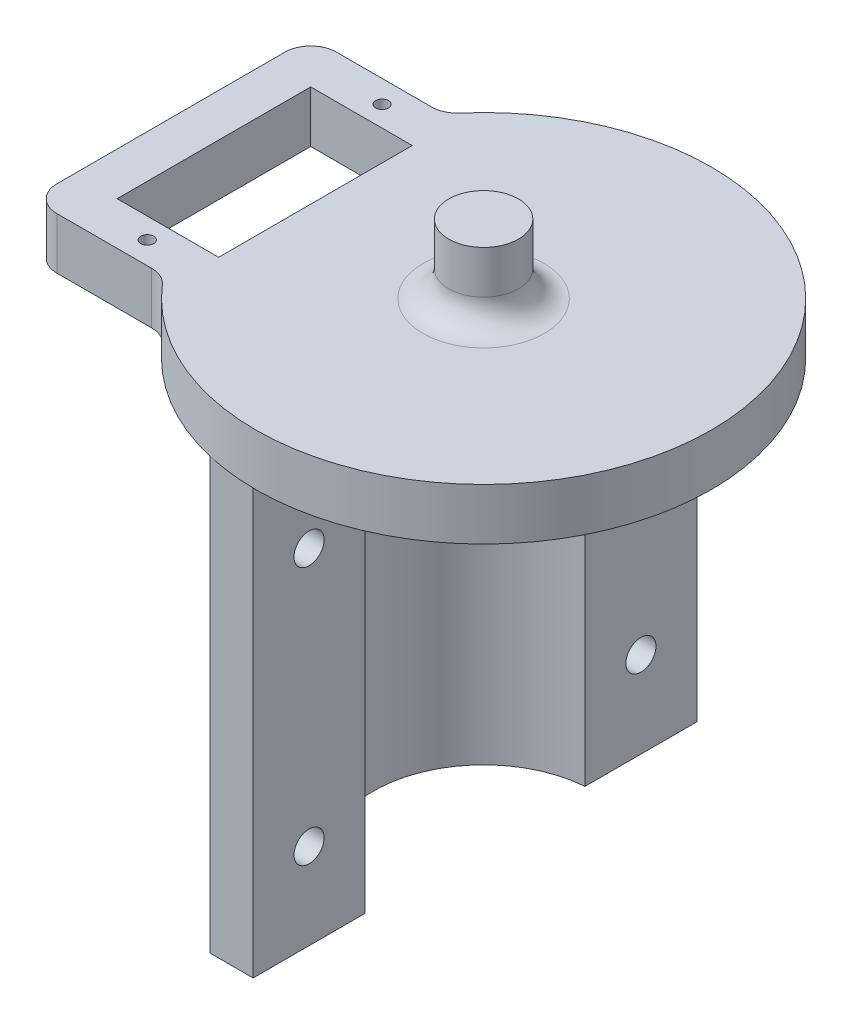
SolidWorks part; units mm, degrees
ref_plane "Front Plane" through (0, 0, 0) normal (0, 0, 1) x (1, 0, 0)
ref_plane "Top Plane" through (0, 0, 0) normal (0, 1, 0) x (1, 0, 0)
ref_plane "Right Plane" through (0, 0, 0) normal (1, 0, 0) x (0, 0, -1)
sketch "Sketch6" plane through (0, 0, 0) normal (0, -1, 0) x (1, 0, 0)
  line L5 (-1, 25.7848) -> (-1, 12.786)
  line L6 (-1, 25.7848) -> (-6, 25.7848)
  line L7 (-6, 25.7848) -> (-6, 16.7848)
  line L8 (-6, -16.7848) -> (-6, -25.7848)
  line L9 (-6, -25.7848) -> (-1, -25.7848)
  line L10 (-1, -25.7848) -> (-1, -12.786)
  line L11 (-12.825, 0) -> (-17.825, 0) construction
  arc A0 (-1, 12.786) -> (-1, -12.786) centre (0, 0) ccw
  arc A1 (-6, 16.7848) -> (-6, -16.7848) centre (0, 0) ccw
  dimension "D1" = 25.65
  dimension "D2" = 5
  dimension "D3" = 1
  dimension "D4" = 9
extrude "Boss-Extrude4" add sketch "Sketch6" along normal blind 50
sketch "Sketch7" plane through (-1, 0, 0) normal (1, 0, 0) x (0, 0, -1)
  line L0 (-19.2854, -50) -> (-19.2854, 0) construction
  line L3 (0, 0) -> (0, -50) construction
  line L6 (-25.7848, -25) -> (25.7848, -25) construction
  line L11 (-12.786, 0) -> (-25.7848, 0) construction
  line L12 (-12.786, -50) -> (-25.7848, -50) construction
  line L13 (-25.7848, -50) -> (-25.7848, 0) construction
  line L14 (25.7848, -50) -> (25.7848, 0) construction
  line L15 (-12.786, -50) -> (12.786, -50) construction
  circle A0 centre (-19.2854, -10) radius 1.75
  circle A1 centre (-19.2854, -40) radius 1.75
  circle A2 centre (19.2854, -40) radius 1.75
  circle A3 centre (19.2854, -10) radius 1.75
  dimension "D1" = 10
  dimension "D2" = 3.5
extrude "Cut-Extrude1" cut sketch "Sketch7" against normal through all
sketch "Sketch8" plane through (0, 0, 0) normal (0, 1, 0) x (1, 0, 0)
  line L0 (-25.4436, -13.65) -> (-25.4436, 13.65) construction
  line L1 (-31.3436, -11.25) -> (-19.5436, -11.25)
  line L2 (-31.3436, -11.25) -> (-31.3436, 11.25)
  line L3 (-31.3436, 11.25) -> (-19.5436, 11.25)
  line L4 (-19.5436, -11.25) -> (-19.5436, 11.25)
  line L5 (-33.3436, -16.25) -> (-22.319, -16.25)
  line L6 (-36.3436, -13.25) -> (-36.3436, 13.25)
  line L7 (-33.3436, 16.25) -> (-22.319, 16.25)
  circle A1 centre (-25.4436, 13.65) radius 0.75
  circle A2 centre (-25.4436, -13.65) radius 0.75
  arc A3 (-20.0472, -17.2906) -> (-20.0472, 17.2906) centre (0, 0) ccw
  arc A4 (-33.3436, -16.25) -> (-36.3436, -13.25) centre (-33.3436, -13.25) cw
  arc A5 (-36.3436, 13.25) -> (-33.3436, 16.25) centre (-33.3436, 13.25) cw
  arc A6 (-22.319, 16.25) -> (-20.0472, 17.2906) centre (-22.319, 19.25) ccw
  arc A7 (-22.319, -16.25) -> (-20.0472, -17.2906) centre (-22.319, -19.25) cw
  circle A8 centre (-25.4436, 5.35) radius 5.9 construction
  point P7 (-19.5436, 0)
  point P13 (-25.4436, -11.25)
  point P18 (-25.4436, 0)
  point P24 (-36.3436, 0)
  dimension "D1" = 5
  dimension "D4" = 1.5
  dimension "D7" = 5
  dimension "D8" = 3
  dimension "D9" = 3
  dimension "D10" = 11.8
  dimension "D2" = 11.8
  dimension "D3" = 22.5
  dimension "D5" = 27.3
  dimension "D6" = 26
extrude "Boss-Extrude5" add sketch "Sketch8" along normal blind 6
sketch "Sketch9" plane through (0, 6, 0) normal (0, 1, 0) x (1, 0, 0)
  circle A0 centre (0, 0) radius 4.05
  dimension "D1" = 8.1
extrude "Boss-Extrude6" add sketch "Sketch9" along normal blind 8
fillet "Fillet1" radius 3 1 edges at (0, 6, 4.05)
